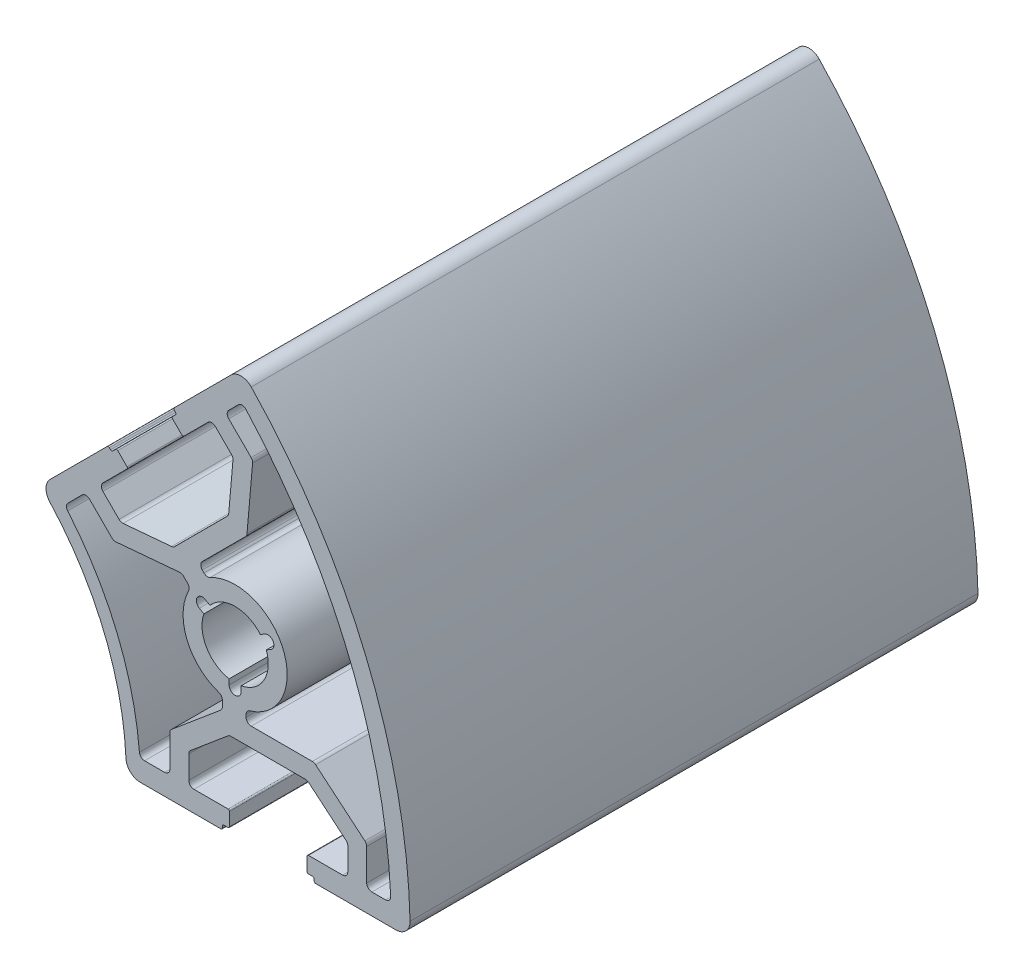
SolidWorks part; units mm, degrees
material "6061 Alaşım"
ref_plane "Ön Düzlem" through (0, 0, 0) normal (0, 0, 1) x (1, 0, 0)
ref_plane "Üst Düzlem" through (0, 0, 0) normal (0, 1, 0) x (1, 0, 0)
ref_plane "Sağ Düzlem" through (0, 0, 0) normal (1, 0, 0) x (0, 0, -1)
sketch "Çizim1" plane through (0, 0, 0) normal (0, 0, 1) x (1, 0, 0)
  line L0 (0, 0) -> (100, 0) construction
  line L1 (0, 0) -> (100, 100) construction
  line L2 (0, 0) -> (56.3567, 23.3437) construction
  line L3 (32.4654, 0) -> (59.4811, 0) construction
  line L4 (41.15, 0.15) -> (41.15, 0.35)
  line L5 (41.3, 0.5) -> (41.75, 0.5)
  line L6 (41.9, 0.65) -> (41.9, 2.05)
  line L7 (41.75, 2.2) -> (38.1456, 2.2)
  line L8 (37.6, 2.7456) -> (37.6, 5.156)
  line L9 (37.7949, 5.5739) -> (41.7258, 8.8724)
  line L10 (42.0765, 9) -> (49.9235, 9)
  line L11 (50.2742, 8.8724) -> (54.2051, 5.5739)
  line L12 (54.4, 5.156) -> (54.4, 2.7456)
  line L13 (53.8544, 2.2) -> (50.25, 2.2)
  line L14 (50.1, 2.05) -> (50.1, 0.65)
  line L15 (50.25, 0.5) -> (50.7, 0.5)
  line L16 (50.85, 0.35) -> (50.85, 0.15)
  line L17 (51, 0) -> (61, 0)
  line L18 (41.15, 11.8622) -> (41.15, 11.2544)
  line L19 (40.9551, 10.8365) -> (35.7949, 6.5065)
  line L20 (35.6, 6.0886) -> (35.6, 2.7456)
  line L21 (35.0544, 2.2) -> (32.9313, 2.2)
  line L22 (44.1956, 11) -> (50.6514, 11)
  line L23 (51.0021, 10.8724) -> (56.2051, 6.5065)
  line L24 (56.4, 6.0886) -> (56.4, 2.7456)
  line L25 (56.9456, 2.2) -> (58.3899, 2.2)
  line L26 (21.9203, 21.9203) -> (43.1335, 43.1335)
  line L27 (46, 0) -> (46, 19.0538) construction
  line L28 (43.65, 11.5456) -> (43.65, 11.801)
  line L29 (30.0261, 12.4372) -> (37.4171, 15.4987) construction
  line L30 (47.5798, 19.7082) -> (54.5089, 22.5783) construction
  line L31 (42.4985, 17.6034) -> (42.4985, 14.1034) construction
  line L32 (42.4985, 14.1034) -> (42.4985, 13.6034) construction
  line L33 (41.8634, 14.1615) -> (41.8634, 13.6034) construction
  line L34 (43.1335, 14.1615) -> (43.1335, 13.6034) construction
  line L35 (39.4674, 19.3534) -> (39.0344, 19.6034) construction
  line L36 (42.4985, 17.6034) -> (39.4674, 19.3534) construction
  line L37 (39.8352, 19.8744) -> (39.3519, 20.1534) construction
  line L38 (39.2002, 18.7744) -> (38.7168, 19.0535) construction
  line L39 (45.5295, 19.3534) -> (45.9626, 19.6034) construction
  line L40 (42.4985, 17.6034) -> (45.5295, 19.3534) construction
  line L41 (45.7968, 18.7744) -> (46.2801, 19.0535) construction
  line L42 (45.1617, 19.8744) -> (45.645, 20.1534) construction
  line L43 (30.0261, 12.4372) -> (28.6403, 11.8632)
  line L44 (54.5089, 22.5783) -> (56.3567, 23.3437)
  line L45 (37.4171, 15.4987) -> (39.2649, 16.264)
  line L46 (47.5798, 19.7082) -> (37.4171, 15.4987)
  line L47 (41, 0) -> (32.4654, 0)
  line L48 (51, 0) -> (59.4811, 0)
  arc A0 (43.1335, 43.1335) -> (61, 0) centre (0, 0) cw construction
  arc A1 (21.9203, 21.9203) -> (31, 0) centre (0, 0) cw construction
  arc A2 (32.5269, 32.5269) -> (46, 0) centre (0, 0) cw construction
  arc A3 (54.5089, 22.5783) -> (58.9349, 2.7712) centre (0, 0) cw
  circle A4 centre (42.4985, 17.6034) radius 3.5 construction
  arc A5 (37.4171, 15.4987) -> (40.7754, 12.3803) centre (42.4985, 17.6034) ccw
  arc A6 (30.0261, 12.4372) -> (32.3876, 2.7002) centre (0, 0) cw
  arc A7 (41.8634, 13.6034) -> (43.1335, 13.6034) centre (42.4985, 13.6034) ccw construction
  arc A8 (39.3519, 20.1534) -> (38.7168, 19.0535) centre (39.0344, 19.6034) ccw construction
  arc A9 (46.2801, 19.0535) -> (45.645, 20.1534) centre (45.9626, 19.6034) ccw construction
  arc A10 (39.8352, 19.8744) -> (45.1617, 19.8744) centre (42.4985, 17.6034) cw construction
  arc A11 (45.7968, 18.7744) -> (43.1335, 14.1615) centre (42.4985, 17.6034) cw construction
  arc A12 (41.8634, 14.1615) -> (39.2002, 18.7744) centre (42.4985, 17.6034) cw construction
  arc A13 (44.0424, 12.3246) -> (47.5798, 19.7082) centre (42.4985, 17.6034) ccw
  arc A14 (41.9, 2.05) -> (41.75, 2.2) centre (41.75, 2.05) ccw
  arc A15 (50.25, 2.2) -> (50.1, 2.05) centre (50.25, 2.05) ccw
  arc A16 (50.85, 0.15) -> (51, 0) centre (51, 0.15) ccw
  arc A17 (50.7, 0.5) -> (50.85, 0.35) centre (50.7, 0.35) cw
  arc A18 (50.1, 0.65) -> (50.25, 0.5) centre (50.25, 0.65) ccw
  arc A19 (41.75, 0.5) -> (41.9, 0.65) centre (41.75, 0.65) ccw
  arc A20 (41.15, 0.35) -> (41.3, 0.5) centre (41.3, 0.35) cw
  arc A21 (41, 0) -> (41.15, 0.15) centre (41, 0.15) ccw
  arc A22 (58.9349, 2.7712) -> (58.3899, 2.2) centre (58.3899, 2.7456) cw
  arc A23 (56.4, 2.7456) -> (56.9456, 2.2) centre (56.9456, 2.7456) ccw
  arc A24 (56.2051, 6.5065) -> (56.4, 6.0886) centre (55.8544, 6.0886) cw
  arc A25 (43.65, 11.801) -> (44.0424, 12.3246) centre (44.1956, 11.801) cw
  arc A26 (44.1956, 11) -> (43.65, 11.5456) centre (44.1956, 11.5456) cw
  arc A27 (50.6514, 11) -> (51.0021, 10.8724) centre (50.6514, 10.4544) cw
  arc A28 (41.15, 11.8622) -> (40.7754, 12.3803) centre (40.6044, 11.8622) ccw
  arc A29 (41.15, 11.2544) -> (40.9551, 10.8365) centre (40.6044, 11.2544) cw
  arc A30 (35.7949, 6.5065) -> (35.6, 6.0886) centre (36.1456, 6.0886) ccw
  arc A31 (32.3876, 2.7002) -> (32.9313, 2.2) centre (32.9313, 2.7456) ccw
  arc A32 (35.6, 2.7456) -> (35.0544, 2.2) centre (35.0544, 2.7456) cw
  arc A33 (38.1456, 2.2) -> (37.6, 2.7456) centre (38.1456, 2.7456) cw
  arc A34 (54.4, 2.7456) -> (53.8544, 2.2) centre (53.8544, 2.7456) cw
  arc A35 (54.2051, 5.5739) -> (54.4, 5.156) centre (53.8544, 5.156) cw
  arc A36 (37.6, 5.156) -> (37.7949, 5.5739) centre (38.1456, 5.156) cw
  arc A37 (41.7258, 8.8724) -> (42.0765, 9) centre (42.0765, 8.4544) cw
  arc A38 (49.9235, 9) -> (50.2742, 8.8724) centre (49.9235, 8.4544) cw
  arc A39 (28.6403, 11.8632) -> (30.967, 1.4308) centre (0, 0) cw
  arc A40 (56.3567, 23.3437) -> (60.9806, 1.5378) centre (0, 0) cw
  arc A41 (30.967, 1.4308) -> (32.4654, 0) centre (32.4654, 1.5) ccw
  arc A42 (59.4811, 0) -> (60.9806, 1.5378) centre (59.4811, 1.5) ccw
  point P64 (42.4985, 17.6034)
  point P68 (41.9, 2.2)
  point P71 (50.1, 2.2)
  point P74 (50.85, 0)
  point P77 (50.85, 0.5)
  point P80 (50.1, 0.5)
  point P83 (41.9, 0.5)
  point P86 (41.15, 0.5)
  point P89 (41.15, 0)
  point P98 (43.65, 12.2253)
  point P107 (41.15, 11)
  point P116 (37.6, 2.2)
  point P119 (54.4, 2.2)
  point P122 (54.4, 5.4104)
  point P125 (37.6, 5.4104)
  dimension "D3" = 61
  dimension "D4" = 31
  dimension "D23" = 2
  dimension "D24" = 7
  dimension "D25" = 11
  dimension "D27" = 32.5
  dimension "D28" = 0.5
  dimension "D30" = 0.15
  dimension "D31" = 0.5456
  dimension "D32" = 1.5
  dimension "D1" = 45
  dimension "D2" = 100
  dimension "D5" = 8.2
  dimension "D6" = 4.1
  dimension "D7" = 0.75
  dimension "D8" = 0.5
  dimension "D9" = 2.2
  dimension "D10" = 2.2
  dimension "D11" = 0.75
  dimension "D12" = 0.5
  dimension "D13" = 130
  dimension "D14" = 130
  dimension "D15" = 9
  dimension "D16" = 4.3
  dimension "D17" = 4.3
  dimension "D18" = 2
  dimension "D19" = 2
  dimension "D20" = 2
  dimension "D21" = 2
  dimension "D22" = 2
  dimension "D26" = 2.5
  dimension "D29" = 3
sketch "Çizim3" plane through (0, 0, 0) normal (0, 0, 1) x (1, 0, 0)
  line L0 (51, 0) -> (59.4811, 0) construction
  line L1 (54.5089, 22.5783) -> (56.3567, 23.3437) construction
  line L2 (56.9456, 2.2) -> (58.3899, 2.2) construction
  line L3 (56.4, 6.0886) -> (56.4, 2.7456) construction
  line L4 (51.0021, 10.8724) -> (56.2051, 6.5065) construction
  line L5 (44.1956, 11) -> (50.6514, 11) construction
  line L6 (43.65, 11.5456) -> (43.65, 11.801) construction
  line L7 (47.5798, 19.7082) -> (37.4171, 15.4987) construction
  line L8 (51, 0) -> (59.4811, 0)
  line L9 (54.5089, 22.5783) -> (56.3567, 23.3437) construction
  line L10 (56.9456, 2.2) -> (58.3899, 2.2)
  line L11 (56.4, 6.0886) -> (56.4, 2.7456)
  line L12 (51.0021, 10.8724) -> (56.2051, 6.5065)
  line L13 (44.1956, 11) -> (50.6514, 11)
  line L14 (43.65, 11.5456) -> (43.65, 11.801)
  line L15 (47.5798, 19.7082) -> (37.4171, 15.4987)
  line L16 (50.85, 0.35) -> (50.85, 0.15) construction
  line L17 (50.25, 0.5) -> (50.7, 0.5) construction
  line L18 (50.1, 2.05) -> (50.1, 0.65) construction
  line L19 (53.8544, 2.2) -> (50.25, 2.2) construction
  line L20 (54.4, 5.156) -> (54.4, 2.7456) construction
  line L21 (50.2742, 8.8724) -> (54.2051, 5.5739) construction
  line L22 (42.0765, 9) -> (49.9235, 9) construction
  line L23 (37.7949, 5.5739) -> (41.7258, 8.8724) construction
  line L24 (37.6, 2.7456) -> (37.6, 5.156) construction
  line L25 (41.75, 2.2) -> (38.1456, 2.2) construction
  line L26 (41.9, 0.65) -> (41.9, 2.05) construction
  line L27 (41.3, 0.5) -> (41.75, 0.5) construction
  line L28 (41.15, 0.15) -> (41.15, 0.35) construction
  line L29 (41, 0) -> (32.4654, 0) construction
  line L30 (30.0261, 12.4372) -> (28.6403, 11.8632) construction
  line L31 (35.0544, 2.2) -> (32.9313, 2.2) construction
  line L32 (35.6, 6.0886) -> (35.6, 2.7456) construction
  line L33 (40.9551, 10.8365) -> (35.7949, 6.5065) construction
  line L34 (41.15, 11.8622) -> (41.15, 11.2544) construction
  line L35 (50.85, 0.35) -> (50.85, 0.15)
  line L36 (50.25, 0.5) -> (50.7, 0.5)
  line L37 (50.1, 2.05) -> (50.1, 0.65)
  line L38 (53.8544, 2.2) -> (50.25, 2.2)
  line L39 (54.4, 5.156) -> (54.4, 2.7456)
  line L40 (50.2742, 8.8724) -> (54.2051, 5.5739)
  line L41 (42.0765, 9) -> (49.9235, 9)
  line L42 (37.7949, 5.5739) -> (41.7258, 8.8724)
  line L43 (37.6, 2.7456) -> (37.6, 5.156)
  line L44 (41.75, 2.2) -> (38.1456, 2.2)
  line L45 (41.9, 0.65) -> (41.9, 2.05)
  line L46 (41.3, 0.5) -> (41.75, 0.5)
  line L47 (41.15, 0.15) -> (41.15, 0.35)
  line L48 (41, 0) -> (32.4654, 0)
  line L49 (30.0261, 12.4372) -> (28.6403, 11.8632) construction
  line L50 (35.0544, 2.2) -> (32.9313, 2.2)
  line L51 (35.6, 6.0886) -> (35.6, 2.7456)
  line L52 (40.9551, 10.8365) -> (35.7949, 6.5065)
  line L53 (41.15, 11.8622) -> (41.15, 11.2544)
  line L54 (36.2039, 35.7089) -> (36.0624, 35.8503)
  line L55 (35.8857, 35.1786) -> (36.2039, 35.4968)
  line L56 (36.8756, 33.9765) -> (35.8857, 34.9664)
  line L57 (39.6365, 36.5252) -> (37.0878, 33.9765)
  line L58 (42.1124, 34.8208) -> (40.408, 36.5252)
  line L59 (41.8229, 29.2755) -> (42.2702, 34.3875)
  line L60 (36.1165, 23.3886) -> (41.6652, 28.9373)
  line L61 (30.6664, 22.7837) -> (35.7783, 23.2309)
  line L62 (28.5286, 24.6458) -> (30.233, 22.9414)
  line L63 (31.0773, 27.9661) -> (28.5286, 25.4174)
  line L64 (30.0874, 29.1682) -> (31.0773, 28.1782)
  line L65 (29.5571, 28.85) -> (29.8753, 29.1682)
  line L66 (29.2035, 28.9914) -> (29.3449, 28.85)
  line L67 (28.9914, 28.9914) -> (22.9565, 22.9565)
  line L68 (26.3429, 23.2316) -> (24.8416, 21.7303)
  line L69 (29.4783, 20.8677) -> (27.1144, 23.2316)
  line L70 (36.6222, 21.2971) -> (29.9116, 20.71)
  line L71 (37.4853, 20.7096) -> (37.0555, 21.1394)
  line L72 (39.0292, 22.7013) -> (39.2098, 22.5207)
  line L73 (39.0292, 23.4728) -> (43.5941, 28.0378)
  line L74 (43.7519, 28.376) -> (44.3438, 35.1422)
  line L75 (44.1861, 35.5755) -> (41.8222, 37.9394)
  line L76 (41.8222, 38.711) -> (42.8435, 39.7323)
  line L77 (36.0624, 36.0624) -> (42.0595, 42.0595)
  line L78 (45.1617, 19.8744) -> (45.645, 20.1534) construction
  line L79 (45.7968, 18.7744) -> (46.2801, 19.0535) construction
  line L80 (43.1335, 14.1615) -> (43.1335, 13.6034) construction
  line L81 (41.8634, 14.1615) -> (41.8634, 13.6034) construction
  line L82 (39.2002, 18.7744) -> (38.7168, 19.0535) construction
  line L83 (39.8352, 19.8744) -> (39.3519, 20.1534) construction
  line L84 (45.1617, 19.8744) -> (45.645, 20.1534)
  line L85 (45.7968, 18.7744) -> (46.2801, 19.0535)
  line L86 (43.1335, 14.1615) -> (43.1335, 13.6034)
  line L87 (41.8634, 14.1615) -> (41.8634, 13.6034)
  line L88 (39.2002, 18.7744) -> (38.7168, 19.0535)
  line L89 (39.8352, 19.8744) -> (39.3519, 20.1534)
  arc A0 (59.4811, 0) -> (60.9806, 1.5378) centre (59.4811, 1.5) ccw construction
  arc A1 (60.9806, 1.5378) -> (56.3567, 23.3437) centre (0, 0) ccw construction
  arc A2 (58.9349, 2.7712) -> (54.5089, 22.5783) centre (0, 0) ccw construction
  arc A3 (58.3899, 2.2) -> (58.9349, 2.7712) centre (58.3899, 2.7456) ccw construction
  arc A4 (56.4, 2.7456) -> (56.9456, 2.2) centre (56.9456, 2.7456) ccw construction
  arc A5 (56.4, 6.0886) -> (56.2051, 6.5065) centre (55.8544, 6.0886) ccw construction
  arc A6 (51.0021, 10.8724) -> (50.6514, 11) centre (50.6514, 10.4544) ccw construction
  arc A7 (43.65, 11.5456) -> (44.1956, 11) centre (44.1956, 11.5456) ccw construction
  arc A8 (44.0424, 12.3246) -> (43.65, 11.801) centre (44.1956, 11.801) ccw construction
  arc A9 (44.0424, 12.3246) -> (47.5798, 19.7082) centre (42.4985, 17.6034) ccw construction
  arc A10 (59.4811, 0) -> (60.9806, 1.5378) centre (59.4811, 1.5) ccw
  arc A11 (60.9806, 1.5378) -> (44.2072, 42.0324) centre (0, 0) ccw
  arc A12 (58.9349, 2.7712) -> (43.6328, 39.7137) centre (0, 0) ccw
  arc A13 (58.3899, 2.2) -> (58.9349, 2.7712) centre (58.3899, 2.7456) ccw
  arc A14 (56.4, 2.7456) -> (56.9456, 2.2) centre (56.9456, 2.7456) ccw
  arc A15 (56.4, 6.0886) -> (56.2051, 6.5065) centre (55.8544, 6.0886) ccw
  arc A16 (51.0021, 10.8724) -> (50.6514, 11) centre (50.6514, 10.4544) ccw
  arc A17 (43.65, 11.5456) -> (44.1956, 11) centre (44.1956, 11.5456) ccw
  arc A18 (44.0424, 12.3246) -> (43.65, 11.801) centre (44.1956, 11.801) ccw
  arc A19 (44.0424, 12.3246) -> (39.8575, 22.4279) centre (42.4985, 17.6034) ccw
  arc A20 (50.85, 0.15) -> (51, 0) centre (51, 0.15) ccw construction
  arc A21 (50.85, 0.35) -> (50.7, 0.5) centre (50.7, 0.35) ccw construction
  arc A22 (50.1, 0.65) -> (50.25, 0.5) centre (50.25, 0.65) ccw construction
  arc A23 (50.25, 2.2) -> (50.1, 2.05) centre (50.25, 2.05) ccw construction
  arc A24 (53.8544, 2.2) -> (54.4, 2.7456) centre (53.8544, 2.7456) ccw construction
  arc A25 (54.4, 5.156) -> (54.2051, 5.5739) centre (53.8544, 5.156) ccw construction
  arc A26 (50.2742, 8.8724) -> (49.9235, 9) centre (49.9235, 8.4544) ccw construction
  arc A27 (42.0765, 9) -> (41.7258, 8.8724) centre (42.0765, 8.4544) ccw construction
  arc A28 (37.7949, 5.5739) -> (37.6, 5.156) centre (38.1456, 5.156) ccw construction
  arc A29 (37.6, 2.7456) -> (38.1456, 2.2) centre (38.1456, 2.7456) ccw construction
  arc A30 (41.9, 2.05) -> (41.75, 2.2) centre (41.75, 2.05) ccw construction
  arc A31 (41.75, 0.5) -> (41.9, 0.65) centre (41.75, 0.65) ccw construction
  arc A32 (41.3, 0.5) -> (41.15, 0.35) centre (41.3, 0.35) ccw construction
  arc A33 (41, 0) -> (41.15, 0.15) centre (41, 0.15) ccw construction
  arc A34 (30.967, 1.4308) -> (32.4654, 0) centre (32.4654, 1.5) ccw construction
  arc A35 (30.967, 1.4308) -> (28.6403, 11.8632) centre (0, 0) ccw construction
  arc A36 (32.3876, 2.7002) -> (30.0261, 12.4372) centre (0, 0) ccw construction
  arc A37 (32.3876, 2.7002) -> (32.9313, 2.2) centre (32.9313, 2.7456) ccw construction
  arc A38 (35.0544, 2.2) -> (35.6, 2.7456) centre (35.0544, 2.7456) ccw construction
  arc A39 (35.7949, 6.5065) -> (35.6, 6.0886) centre (36.1456, 6.0886) ccw construction
  arc A40 (40.9551, 10.8365) -> (41.15, 11.2544) centre (40.6044, 11.2544) ccw construction
  arc A41 (41.15, 11.8622) -> (40.7754, 12.3803) centre (40.6044, 11.8622) ccw construction
  arc A42 (37.4171, 15.4987) -> (40.7754, 12.3803) centre (42.4985, 17.6034) ccw construction
  arc A43 (50.85, 0.15) -> (51, 0) centre (51, 0.15) ccw
  arc A44 (50.85, 0.35) -> (50.7, 0.5) centre (50.7, 0.35) ccw
  arc A45 (50.1, 0.65) -> (50.25, 0.5) centre (50.25, 0.65) ccw
  arc A46 (50.25, 2.2) -> (50.1, 2.05) centre (50.25, 2.05) ccw
  arc A47 (53.8544, 2.2) -> (54.4, 2.7456) centre (53.8544, 2.7456) ccw
  arc A48 (54.4, 5.156) -> (54.2051, 5.5739) centre (53.8544, 5.156) ccw
  arc A49 (50.2742, 8.8724) -> (49.9235, 9) centre (49.9235, 8.4544) ccw
  arc A50 (42.0765, 9) -> (41.7258, 8.8724) centre (42.0765, 8.4544) ccw
  arc A51 (37.7949, 5.5739) -> (37.6, 5.156) centre (38.1456, 5.156) ccw
  arc A52 (37.6, 2.7456) -> (38.1456, 2.2) centre (38.1456, 2.7456) ccw
  arc A53 (41.9, 2.05) -> (41.75, 2.2) centre (41.75, 2.05) ccw
  arc A54 (41.75, 0.5) -> (41.9, 0.65) centre (41.75, 0.65) ccw
  arc A55 (41.3, 0.5) -> (41.15, 0.35) centre (41.3, 0.35) ccw
  arc A56 (41, 0) -> (41.15, 0.15) centre (41, 0.15) ccw
  arc A57 (30.967, 1.4308) -> (32.4654, 0) centre (32.4654, 1.5) ccw
  arc A58 (30.967, 1.4308) -> (22.9087, 20.8852) centre (0, 0) ccw
  arc A59 (32.3876, 2.7002) -> (24.8109, 20.9922) centre (0, 0) ccw
  arc A60 (32.3876, 2.7002) -> (32.9313, 2.2) centre (32.9313, 2.7456) ccw
  arc A61 (35.0544, 2.2) -> (35.6, 2.7456) centre (35.0544, 2.7456) ccw
  arc A62 (35.7949, 6.5065) -> (35.6, 6.0886) centre (36.1456, 6.0886) ccw
  arc A63 (40.9551, 10.8365) -> (41.15, 11.2544) centre (40.6044, 11.2544) ccw
  arc A64 (41.15, 11.8622) -> (40.7754, 12.3803) centre (40.6044, 11.8622) ccw
  arc A65 (37.5867, 20.0783) -> (40.7754, 12.3803) centre (42.4985, 17.6034) ccw
  arc A66 (36.0624, 35.8503) -> (36.0624, 36.0624) centre (36.1685, 35.9564) cw
  arc A67 (36.2039, 35.7089) -> (36.2039, 35.4968) centre (36.0978, 35.6028) cw
  arc A68 (35.8857, 34.9664) -> (35.8857, 35.1786) centre (35.9917, 35.0725) cw
  arc A69 (37.0878, 33.9765) -> (36.8756, 33.9765) centre (36.9817, 34.0825) cw
  arc A70 (39.6365, 36.5252) -> (40.408, 36.5252) centre (40.0222, 36.1394) cw
  arc A71 (42.1124, 34.8208) -> (42.2702, 34.3875) centre (41.7267, 34.435) cw
  arc A72 (41.8229, 29.2755) -> (41.6652, 28.9373) centre (41.2794, 29.3231) cw
  arc A73 (36.1165, 23.3886) -> (35.7783, 23.2309) centre (35.7308, 23.7744) cw
  arc A74 (30.6664, 22.7837) -> (30.233, 22.9414) centre (30.6188, 23.3272) cw
  arc A75 (28.5286, 24.6458) -> (28.5286, 25.4174) centre (28.9144, 25.0316) cw
  arc A76 (31.0773, 28.1782) -> (31.0773, 27.9661) centre (30.9713, 28.0721) cw
  arc A77 (29.8753, 29.1682) -> (30.0874, 29.1682) centre (29.9813, 29.0621) cw
  arc A78 (29.5571, 28.85) -> (29.3449, 28.85) centre (29.451, 28.956) cw
  arc A79 (28.9914, 28.9914) -> (29.2035, 28.9914) centre (29.0974, 28.8853) cw
  arc A80 (22.9087, 20.8852) -> (22.9565, 22.9565) centre (24.0171, 21.8958) cw
  arc A81 (24.8109, 20.9922) -> (24.8416, 21.7303) centre (25.2274, 21.3445) cw
  arc A82 (26.3429, 23.2316) -> (27.1144, 23.2316) centre (26.7286, 22.8458) cw
  arc A83 (29.9116, 20.71) -> (29.4783, 20.8677) centre (29.8641, 21.2535) cw
  arc A84 (36.6222, 21.2971) -> (37.0555, 21.1394) centre (36.6697, 20.7536) cw
  arc A85 (37.4853, 20.7096) -> (37.5867, 20.0783) centre (37.0995, 20.3238) cw
  arc A86 (39.8575, 22.4279) -> (39.2098, 22.5207) centre (39.5955, 22.9064) cw
  arc A87 (39.0292, 22.7013) -> (39.0292, 23.4728) centre (39.4149, 23.087) cw
  arc A88 (43.7519, 28.376) -> (43.5941, 28.0378) centre (43.2084, 28.4236) cw
  arc A89 (44.1861, 35.5755) -> (44.3438, 35.1422) centre (43.8003, 35.1898) cw
  arc A90 (41.8222, 37.9394) -> (41.8222, 38.711) centre (42.208, 38.3252) cw
  arc A91 (42.8435, 39.7323) -> (43.6328, 39.7137) centre (43.2293, 39.3465) cw
  arc A92 (42.0595, 42.0595) -> (44.2072, 42.0324) centre (43.1201, 40.9988) cw
  arc A93 (45.1617, 19.8744) -> (39.8352, 19.8744) centre (42.4985, 17.6034) ccw construction
  arc A94 (46.2801, 19.0535) -> (45.645, 20.1534) centre (45.9626, 19.6034) ccw construction
  arc A95 (43.1335, 14.1615) -> (45.7968, 18.7744) centre (42.4985, 17.6034) ccw construction
  arc A96 (41.8634, 13.6034) -> (43.1335, 13.6034) centre (42.4985, 13.6034) ccw construction
  arc A97 (39.2002, 18.7744) -> (41.8634, 14.1615) centre (42.4985, 17.6034) ccw construction
  arc A98 (39.3519, 20.1534) -> (38.7168, 19.0535) centre (39.0344, 19.6034) ccw construction
  arc A99 (45.1617, 19.8744) -> (39.8352, 19.8744) centre (42.4985, 17.6034) ccw
  arc A100 (46.2801, 19.0535) -> (45.645, 20.1534) centre (45.9626, 19.6034) ccw
  arc A101 (43.1335, 14.1615) -> (45.7968, 18.7744) centre (42.4985, 17.6034) ccw
  arc A102 (41.8634, 13.6034) -> (43.1335, 13.6034) centre (42.4985, 13.6034) ccw
  arc A103 (39.2002, 18.7744) -> (41.8634, 14.1615) centre (42.4985, 17.6034) ccw
  arc A104 (39.3519, 20.1534) -> (38.7168, 19.0535) centre (39.0344, 19.6034) ccw
extrude "Yükseklik-Ekstrüzyon1" add sketch "Çizim3" against normal blind 60 contours A92 L77 A66 L54 A67 L55 A68 L56 A69 L57 A70 L58 A71 L59 A72 L60 A73 L61 A74 L62 A75 L63 A76 L64 A77 L65 A78 L66 A79 L67 A80 A58 A57 L48 A56 L47 A55 L46 A54 L45 A53 L44 A52 L43 A51 L42 A50 L41 A49 L40 A48
